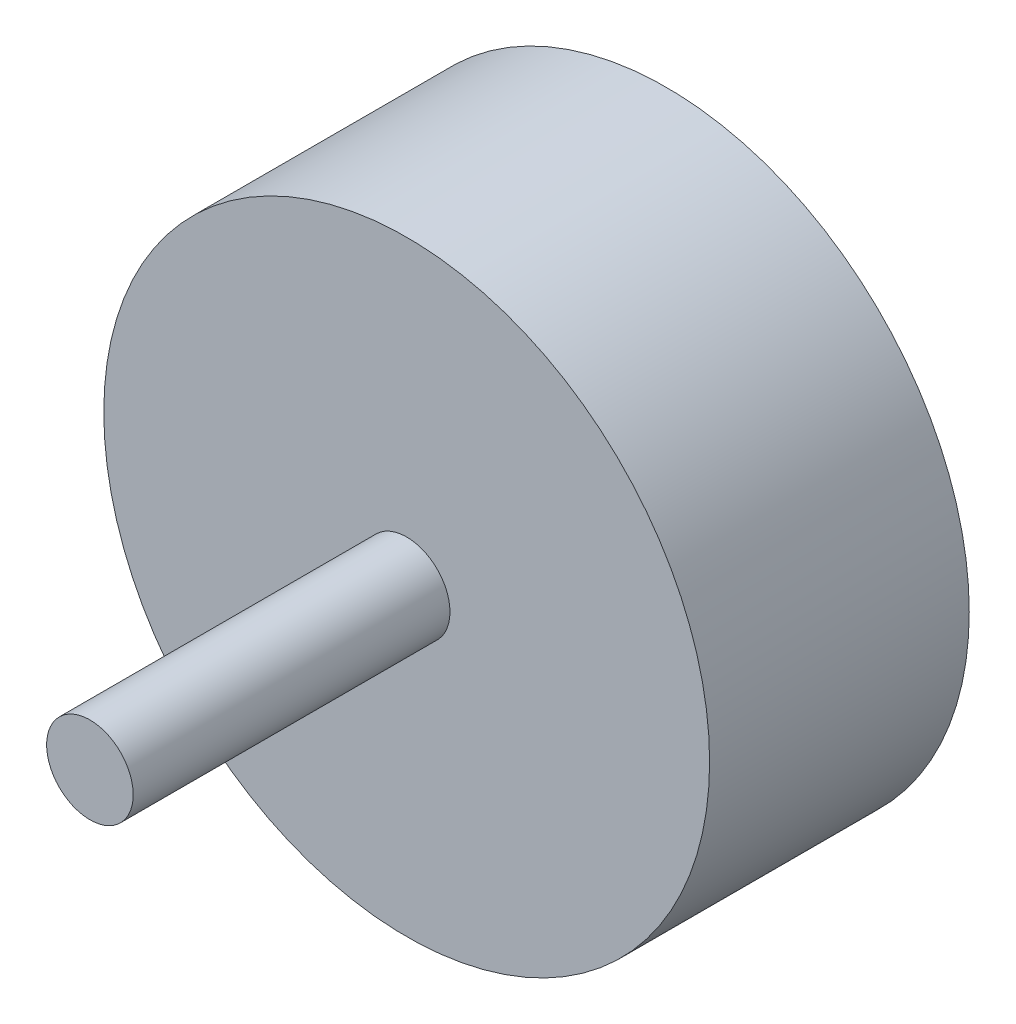
SolidWorks part; units mm, degrees
ref_plane "Front Plane" through (0, 0, 0) normal (0, 0, 1) x (1, 0, 0)
ref_plane "Top Plane" through (0, 0, 0) normal (0, 1, 0) x (1, 0, 0)
ref_plane "Right Plane" through (0, 0, 0) normal (1, 0, 0) x (0, 0, -1)
sketch "Sketch1" plane through (0, 0, 0) normal (0, 0, 1) x (1, 0, 0)
  circle A0 centre (0, 0) radius 88.9
  dimension "D1" = 177.8
extrude "Boss-Extrude1" add sketch "Sketch1" along normal blind 76.2
sketch "Sketch2" plane through (0, 0, 76.2) normal (0, 0, 1) x (1, 0, 0)
  circle A0 centre (0, 0) radius 12.7
  dimension "D1" = 25.4
extrude "Boss-Extrude2" add sketch "Sketch2" along normal blind 92.964
